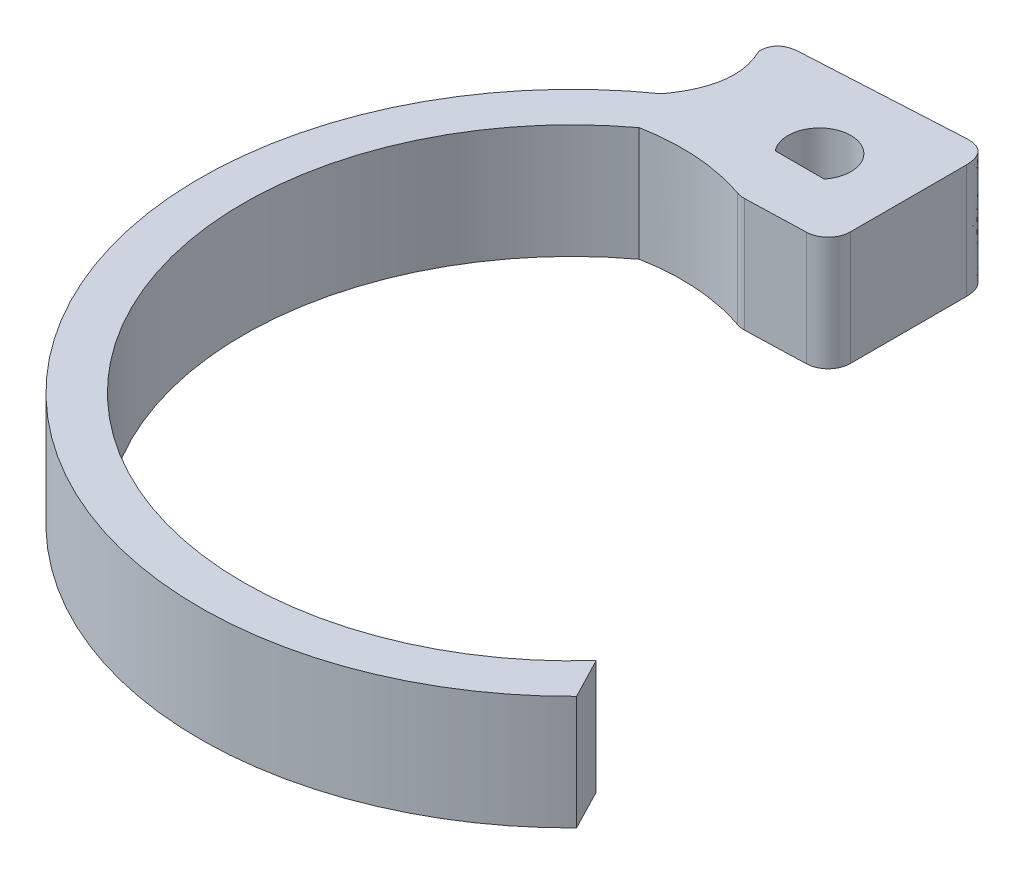
SolidWorks part; units mm, degrees
ref_plane "Front Plane" through (0, 0, 0) normal (0, 0, 1) x (1, 0, 0)
ref_plane "Top Plane" through (0, 0, 0) normal (0, 1, 0) x (1, 0, 0)
ref_plane "Right Plane" through (0, 0, 0) normal (1, 0, 0) x (0, 0, -1)
sketch "Sketch3" plane through (0, 0, 0) normal (0, 1, 0) x (1, 0, 0)
  line L14 (-52.6005, -4.1485) -> (-35.0044, -3.1957)
  line L33 (-32.327, -5.732) -> (-32.327, -18.6639)
  line L34 (-41.4471, -21.34) -> (-34.7305, -21.14)
  line L45 (-2.7732, -78.7206) -> (-5.1348, -74.1673)
  arc A5 (-56.1772, -15.8623) -> (-2.7732, -78.7206) centre (-32.327, -49.7143) ccw
  arc A17 (-32.327, -18.6639) -> (-34.7305, -21.14) centre (-34.8042, -18.6639) cw
  arc A25 (-42.3518, -21.202) -> (-41.4471, -21.34) centre (-41.5227, -18.8011) ccw
  arc A26 (-54.1511, -20.3702) -> (-5.1348, -74.1673) centre (-32.327, -49.7143) ccw
  spline S1 degree 3 poles (-42.3518, -21.202) (-46.1431, -19.8927) (-50.0949, -19.6118) (-54.1511, -20.3702) knots 0.036271 0.036271 0.036271 0.036271 1 1 1 1
  spline S3 degree 2 poles (-54.8663, -6.3089) (-52.5564, -10.9635) (-56.1772, -15.8623) knots 0 0 0 1 1 1
  spline S5 degree 2 poles (-54.8663, -6.3089) (-54.8335, -4.2937) (-52.6005, -4.1485) knots 0 0 0 1 1 1
  spline S7 degree 2 poles (-35.0044, -3.1957) (-32.3914, -3.0291) (-32.327, -5.732) knots 0 0 0 1 1 1
extrude "Boss-Extrude2" add sketch "Sketch3" along normal mid plane 12.7
sketch "Sketch11" plane through (0, -6.35, 0) normal (0, -1, 0) x (-1, 0, 0)
  line L2 (38.8792, -15.0291) -> (44.3286, -15.0291)
  arc A0 (44.3286, -15.0291) -> (38.8792, -15.0291) centre (41.6039, -12.8322) ccw
extrude "Cut-Extrude1" cut sketch "Sketch11" against normal blind 13.208 and the other way blind 0.254
ref_plane "Plane1" through (-39.9746, 19.05, -66.0705) normal (0.9963, 0, -0.0856) x (-0.0856, 0, -0.9963)
